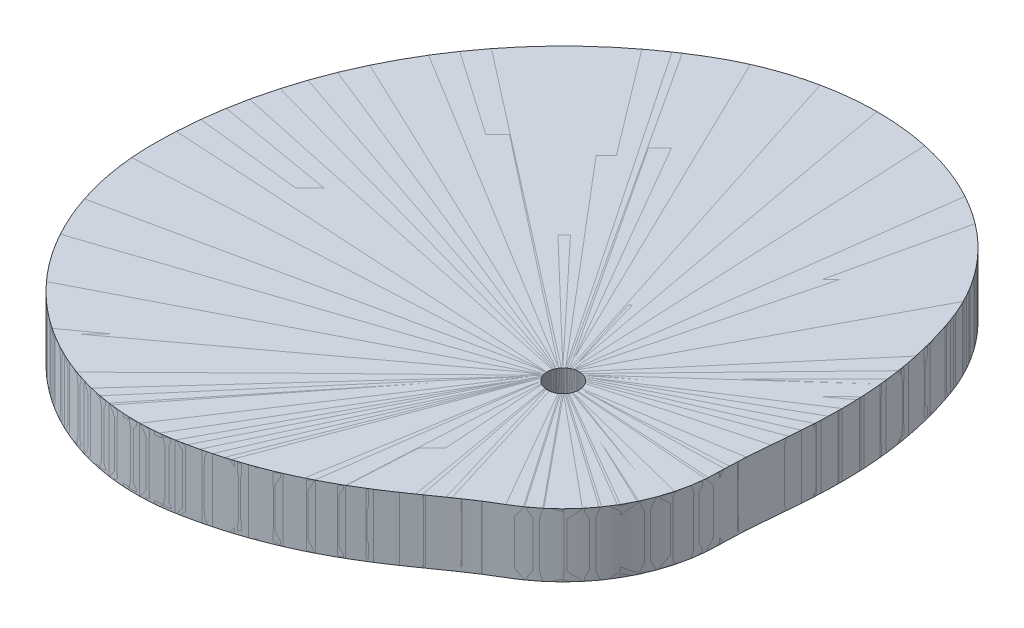
SolidWorks part; units mm, degrees
ref_plane "前视基准面" through (0, 0, 0) normal (0, 0, 1) x (1, 0, 0)
ref_plane "上视基准面" through (0, 0, 0) normal (0, 1, 0) x (1, 0, 0)
ref_plane "右视基准面" through (0, 0, 0) normal (1, 0, 0) x (0, 0, -1)
other "质心 (COM)"
other "Configuration Table"
sketch "草图1" plane through (0, 0, 0) normal (0, 0, 1) x (1, 0, 0)
  line L0 (0, -20200) -> (0, 200) construction
  line L1 (5, 0) -> (130, 0)
  line L2 (130, 0) -> (130, -20)
  line L3 (130, -20) -> (5, -20)
  line L4 (5, -20) -> (5, 0)
revolve "旋转1" add sketch "草图1" angle 360 about L0
sketch "草图2" plane through (0, 0, 0) normal (0, 1, 0) x (1, 0, 0)
  line L0 (0, 0) -> (50, 0) construction
  arc A0 (49.5, 0) -> (49.5868, 4.4012) centre (162.6884, -0.0309) cw
  arc A1 (49.5868, 4.4012) -> (49.8358, 8.9099) centre (194.8962, -1.3625) cw
  arc A2 (49.8358, 8.9099) -> (50.213, 13.6312) centre (319.2819, -10.2396) cw
  arc A3 (50.213, 13.6312) -> (50.663, 18.6649) centre (3915.5987, -329.3799) cw
  arc A4 (50.663, 18.6649) -> (51.1105, 24.1021) centre (-309.0879, 51.0135) ccw
  arc A5 (51.1105, 24.1021) -> (51.462, 30.0213) centre (-145.0959, 38.7218) ccw
  arc A6 (51.462, 30.0213) -> (51.6071, 36.4857) centre (-98.2755, 36.6179) ccw
  arc A7 (51.6071, 36.4857) -> (51.4215, 43.5396) centre (-79.0428, 36.5763) ccw
  arc A8 (51.4215, 43.5396) -> (50.7686, 51.2069) centre (-70.6967, 37.0025) ccw
  arc A9 (50.7686, 51.2069) -> (49.5032, 59.4882) centre (-67.8394, 37.3214) ccw
  arc A10 (49.5032, 59.4882) -> (47.4745, 68.3602) centre (-68.1876, 37.2436) ccw
  arc A11 (47.4745, 68.3602) -> (44.5307, 77.769) centre (-70.5306, 36.6049) ccw
  arc A12 (44.5307, 77.769) -> (40.298, 87.1155) centre (-14.8762, 56.4971) ccw
  arc A13 (40.298, 87.1155) -> (34.5682, 95.7489) centre (-16.8999, 55.3723) ccw
  arc A14 (34.5682, 95.7489) -> (27.4814, 103.4715) centre (-18.8355, 53.855) ccw
  arc A15 (27.4814, 103.4715) -> (19.2044, 110.1045) centre (-20.5276, 52.0448) ccw
  arc A16 (19.2044, 110.1045) -> (9.925, 115.4961) centre (-21.8914, 50.0559) ccw
  arc A17 (9.925, 115.4961) -> (-0.1518, 119.5233) centre (-22.8862, 48.016) ccw
  arc A18 (-0.1518, 119.5233) -> (-10.8076, 122.0939) centre (-23.5139, 46.0515) ccw
  arc A19 (-10.8076, 122.0939) -> (-21.8153, 123.1479) centre (-23.8137, 44.2768) ccw
  arc A20 (-21.8153, 123.1479) -> (-32.943, 122.6584) centre (-23.8548, 42.7851) ccw
  arc A21 (-32.943, 122.6584) -> (-43.9585, 120.6313) centre (-23.7281, 41.6427) ccw
  arc A22 (-43.9585, 120.6313) -> (-54.634, 117.105) centre (-23.5377, 40.8858) ccw
  arc A23 (-54.634, 117.105) -> (-64.75, 112.1503) centre (-23.3663, 40.4621) ccw
  arc A24 (-64.75, 112.1503) -> (-129.5, 0) centre (0, 0) ccw
  arc A25 (-129.5, 0) -> (-128.7329, -11.2381) centre (-46.7244, 0.0047) ccw
  arc A26 (-128.7329, -11.2381) -> (-126.449, -22.2464) centre (-47.177, -0.0586) ccw
  arc A27 (-126.449, -22.2464) -> (-122.6968, -32.7998) centre (-47.9277, -0.2722) ccw
  arc A28 (-122.6968, -32.7998) -> (-117.5569, -42.6814) centre (-48.9804, -0.7337) ccw
  arc A29 (-117.5569, -42.6814) -> (-111.1402, -51.6872) centre (-50.2517, -1.5152) ccw
  arc A30 (-111.1402, -51.6872) -> (-103.5861, -59.6302) centre (-51.6388, -2.6621) ccw
  arc A31 (-103.5861, -59.6302) -> (-95.0601, -66.3433) centre (-53.0262, -4.1879) ccw
  arc A32 (-95.0601, -66.3433) -> (-85.7511, -71.6838) centre (-54.2954, -6.0694) ccw
  arc A33 (-85.7511, -71.6838) -> (-75.8682, -75.5353) centre (-55.3359, -8.2449) ccw
  arc A34 (-75.8682, -75.5353) -> (-65.6369, -77.8113) centre (-56.0575, -10.6155) ccw
  arc A35 (-65.6369, -77.8113) -> (-55.2952, -78.4568) centre (-56.4038, -13.0504) ccw
  arc A36 (-55.2952, -78.4568) -> (-45.0846, -77.4492) centre (-56.366, -15.3653) ccw
  arc A37 (-45.0846, -77.4492) -> (-35.4644, -75.2942) centre (-66.9661, 42.7788) ccw
  arc A38 (-35.4644, -75.2942) -> (-26.7667, -72.6152) centre (-66.3477, 40.4304) ccw
  arc A39 (-26.7667, -72.6152) -> (-18.9621, -69.5703) centre (-66.241, 40.09) ccw
  arc A40 (-18.9621, -69.5703) -> (-11.9957, -66.3021) centre (-67.3934, 42.7239) ccw
  arc A41 (-11.9957, -66.3021) -> (-5.794, -62.9359) centre (-71.1974, 50.1649) ccw
  arc A42 (-5.794, -62.9359) -> (-0.2683, -59.578) centre (-80.8498, 66.8001) ccw
  arc A43 (-0.2683, -59.578) -> (4.6822, -56.314) centre (-106.082, 106.2959) ccw
  arc A44 (4.6822, -56.314) -> (9.1672, -53.2079) centre (-198.7229, 242.1712) ccw
  arc A45 (9.1672, -53.2079) -> (13.3016, -50.3013) centre (2243.0507, -3226.318) cw
  arc A46 (13.3016, -50.3013) -> (17.2017, -47.614) centre (168.5087, -271.3864) cw
  arc A47 (17.2017, -47.614) -> (20.9819, -45.144) centre (98.6281, -168.1038) cw
  arc A48 (20.9819, -45.144) -> (24.75, -42.8683) centre (81.371, -140.8768) cw
  arc A49 (24.75, -42.8683) -> (49.5, 0) centre (0, 0) ccw
extrude "切除-拉伸1" cut sketch "草图2" along normal blind 10 and the other way blind 30 flip side to cut
sketch "草图3" plane through (0, 0, 0) normal (0, 1, 0) x (1, 0, 0)
  circle A0 centre (0, 0) radius 5 construction
  circle A1 centre (0, 0) radius 5
  arc A50 (24.75, -42.8683) -> (20.9819, -45.144) centre (81.371, -140.8768) ccw
  arc A51 (24.75, -42.8683) -> (49.5, 0) centre (0, 0) ccw
  arc A52 (49.5868, 4.4012) -> (49.5, 0) centre (162.6884, -0.0309) ccw
  arc A53 (49.8358, 8.9099) -> (49.5868, 4.4012) centre (194.8962, -1.3625) ccw
  arc A54 (50.213, 13.6312) -> (49.8358, 8.9099) centre (319.2819, -10.2396) ccw
  arc A55 (50.663, 18.6649) -> (50.213, 13.6312) centre (3915.5987, -329.3799) ccw
  arc A56 (50.663, 18.6649) -> (51.1105, 24.1021) centre (-309.0879, 51.0135) ccw
  arc A57 (51.1105, 24.1021) -> (51.462, 30.0213) centre (-145.0959, 38.7218) ccw
  arc A58 (51.462, 30.0213) -> (51.6071, 36.4857) centre (-98.2755, 36.6179) ccw
  arc A59 (51.6071, 36.4857) -> (51.4215, 43.5396) centre (-79.0428, 36.5763) ccw
  arc A60 (51.4215, 43.5396) -> (50.7686, 51.2069) centre (-70.6967, 37.0025) ccw
  arc A61 (50.7686, 51.2069) -> (49.5032, 59.4882) centre (-67.8394, 37.3214) ccw
  arc A62 (49.5032, 59.4882) -> (47.4745, 68.3602) centre (-68.1876, 37.2436) ccw
  arc A63 (47.4745, 68.3602) -> (44.5307, 77.769) centre (-70.5306, 36.6049) ccw
  arc A64 (44.5307, 77.769) -> (40.298, 87.1155) centre (-14.8762, 56.4971) ccw
  arc A65 (40.298, 87.1155) -> (34.5682, 95.7489) centre (-16.8999, 55.3723) ccw
  arc A66 (34.5682, 95.7489) -> (27.4814, 103.4715) centre (-18.8355, 53.855) ccw
  arc A67 (27.4814, 103.4715) -> (19.2044, 110.1045) centre (-20.5276, 52.0448) ccw
  arc A68 (19.2044, 110.1045) -> (9.925, 115.4961) centre (-21.8914, 50.0559) ccw
  arc A69 (9.925, 115.4961) -> (-0.1518, 119.5233) centre (-22.8862, 48.016) ccw
  arc A70 (-0.1518, 119.5233) -> (-10.8076, 122.0939) centre (-23.5139, 46.0515) ccw
  arc A71 (-10.8076, 122.0939) -> (-21.8153, 123.1479) centre (-23.8137, 44.2768) ccw
  arc A72 (-21.8153, 123.1479) -> (-32.943, 122.6584) centre (-23.8548, 42.7851) ccw
  arc A73 (-32.943, 122.6584) -> (-43.9585, 120.6313) centre (-23.7281, 41.6427) ccw
  arc A74 (-43.9585, 120.6313) -> (-54.634, 117.105) centre (-23.5377, 40.8858) ccw
  arc A75 (-54.634, 117.105) -> (-64.75, 112.1503) centre (-23.3663, 40.4621) ccw
  arc A76 (-64.75, 112.1503) -> (-129.5, 0) centre (0, 0) ccw
  arc A77 (-129.5, 0) -> (-128.7329, -11.2381) centre (-46.7244, 0.0047) ccw
  arc A78 (-128.7329, -11.2381) -> (-126.449, -22.2464) centre (-47.177, -0.0586) ccw
  arc A79 (-126.449, -22.2464) -> (-122.6968, -32.7998) centre (-47.9277, -0.2722) ccw
  arc A80 (-122.6968, -32.7998) -> (-117.5569, -42.6814) centre (-48.9804, -0.7337) ccw
  arc A81 (-117.5569, -42.6814) -> (-111.1402, -51.6872) centre (-50.2517, -1.5152) ccw
  arc A82 (-111.1402, -51.6872) -> (-103.5861, -59.6302) centre (-51.6388, -2.6621) ccw
  arc A83 (-103.5861, -59.6302) -> (-95.0601, -66.3433) centre (-53.0262, -4.1879) ccw
  arc A84 (-95.0601, -66.3433) -> (-85.7511, -71.6838) centre (-54.2954, -6.0694) ccw
  arc A85 (-85.7511, -71.6838) -> (-75.8682, -75.5353) centre (-55.3359, -8.2449) ccw
  arc A86 (-75.8682, -75.5353) -> (-65.6369, -77.8113) centre (-56.0575, -10.6155) ccw
  arc A87 (-65.6369, -77.8113) -> (-55.2952, -78.4568) centre (-56.4038, -13.0504) ccw
  arc A88 (-55.2952, -78.4568) -> (-45.0846, -77.4492) centre (-56.366, -15.3653) ccw
  arc A89 (-45.0846, -77.4492) -> (-35.4644, -75.2942) centre (-66.9661, 42.7788) ccw
  arc A90 (-35.4644, -75.2942) -> (-26.7667, -72.6152) centre (-66.3477, 40.4304) ccw
  arc A91 (-26.7667, -72.6152) -> (-18.9621, -69.5703) centre (-66.241, 40.09) ccw
  arc A92 (-18.9621, -69.5703) -> (-11.9957, -66.3021) centre (-67.3934, 42.7239) ccw
  arc A93 (-11.9957, -66.3021) -> (-5.794, -62.9359) centre (-71.1974, 50.1649) ccw
  arc A94 (-5.794, -62.9359) -> (-0.2683, -59.578) centre (-80.8498, 66.8001) ccw
  arc A95 (-0.2683, -59.578) -> (4.6822, -56.314) centre (-106.082, 106.2959) ccw
  arc A96 (4.6822, -56.314) -> (9.1672, -53.2079) centre (-198.7229, 242.1712) ccw
  arc A97 (13.3016, -50.3013) -> (9.1672, -53.2079) centre (2243.0507, -3226.318) ccw
  arc A98 (17.2017, -47.614) -> (13.3016, -50.3013) centre (168.5087, -271.3864) ccw
  arc A99 (20.9819, -45.144) -> (17.2017, -47.614) centre (98.6281, -168.1038) ccw
  arc A100 (24.75, -42.8683) -> (20.9819, -45.144) centre (81.371, -140.8768) ccw construction
  arc A101 (24.75, -42.8683) -> (49.5, 0) centre (0, 0) ccw construction
  arc A102 (49.5868, 4.4012) -> (49.5, 0) centre (162.6884, -0.0309) ccw construction
  arc A103 (49.8358, 8.9099) -> (49.5868, 4.4012) centre (194.8962, -1.3625) ccw construction
  arc A104 (50.213, 13.6312) -> (49.8358, 8.9099) centre (319.2819, -10.2396) ccw construction
  arc A105 (50.663, 18.6649) -> (50.213, 13.6312) centre (3915.5987, -329.3799) ccw construction
  arc A106 (50.663, 18.6649) -> (51.1105, 24.1021) centre (-309.0879, 51.0135) ccw construction
  arc A107 (51.1105, 24.1021) -> (51.462, 30.0213) centre (-145.0959, 38.7218) ccw construction
  arc A108 (51.462, 30.0213) -> (51.6071, 36.4857) centre (-98.2755, 36.6179) ccw construction
  arc A109 (51.6071, 36.4857) -> (51.4215, 43.5396) centre (-79.0428, 36.5763) ccw construction
  arc A110 (51.4215, 43.5396) -> (50.7686, 51.2069) centre (-70.6967, 37.0025) ccw construction
  arc A111 (50.7686, 51.2069) -> (49.5032, 59.4882) centre (-67.8394, 37.3214) ccw construction
  arc A112 (49.5032, 59.4882) -> (47.4745, 68.3602) centre (-68.1876, 37.2436) ccw construction
  arc A113 (47.4745, 68.3602) -> (44.5307, 77.769) centre (-70.5306, 36.6049) ccw construction
  arc A114 (44.5307, 77.769) -> (40.298, 87.1155) centre (-14.8762, 56.4971) ccw construction
  arc A115 (40.298, 87.1155) -> (34.5682, 95.7489) centre (-16.8999, 55.3723) ccw construction
  arc A116 (34.5682, 95.7489) -> (27.4814, 103.4715) centre (-18.8355, 53.855) ccw construction
  arc A117 (27.4814, 103.4715) -> (19.2044, 110.1045) centre (-20.5276, 52.0448) ccw construction
  arc A118 (19.2044, 110.1045) -> (9.925, 115.4961) centre (-21.8914, 50.0559) ccw construction
  arc A119 (9.925, 115.4961) -> (-0.1518, 119.5233) centre (-22.8862, 48.016) ccw construction
  arc A120 (-0.1518, 119.5233) -> (-10.8076, 122.0939) centre (-23.5139, 46.0515) ccw construction
  arc A121 (-10.8076, 122.0939) -> (-21.8153, 123.1479) centre (-23.8137, 44.2768) ccw construction
  arc A122 (-21.8153, 123.1479) -> (-32.943, 122.6584) centre (-23.8548, 42.7851) ccw construction
  arc A123 (-32.943, 122.6584) -> (-43.9585, 120.6313) centre (-23.7281, 41.6427) ccw construction
  arc A124 (-43.9585, 120.6313) -> (-54.634, 117.105) centre (-23.5377, 40.8858) ccw construction
  arc A125 (-54.634, 117.105) -> (-64.75, 112.1503) centre (-23.3663, 40.4621) ccw construction
  arc A126 (-64.75, 112.1503) -> (-129.5, 0) centre (0, 0) ccw construction
  arc A127 (-129.5, 0) -> (-128.7329, -11.2381) centre (-46.7244, 0.0047) ccw construction
  arc A128 (-128.7329, -11.2381) -> (-126.449, -22.2464) centre (-47.177, -0.0586) ccw construction
  arc A129 (-126.449, -22.2464) -> (-122.6968, -32.7998) centre (-47.9277, -0.2722) ccw construction
  arc A130 (-122.6968, -32.7998) -> (-117.5569, -42.6814) centre (-48.9804, -0.7337) ccw construction
  arc A131 (-117.5569, -42.6814) -> (-111.1402, -51.6872) centre (-50.2517, -1.5152) ccw construction
  arc A132 (-111.1402, -51.6872) -> (-103.5861, -59.6302) centre (-51.6388, -2.6621) ccw construction
  arc A133 (-103.5861, -59.6302) -> (-95.0601, -66.3433) centre (-53.0262, -4.1879) ccw construction
  arc A134 (-95.0601, -66.3433) -> (-85.7511, -71.6838) centre (-54.2954, -6.0694) ccw construction
  arc A135 (-85.7511, -71.6838) -> (-75.8682, -75.5353) centre (-55.3359, -8.2449) ccw construction
  arc A136 (-75.8682, -75.5353) -> (-65.6369, -77.8113) centre (-56.0575, -10.6155) ccw construction
  arc A137 (-65.6369, -77.8113) -> (-55.2952, -78.4568) centre (-56.4038, -13.0504) ccw construction
  arc A138 (-55.2952, -78.4568) -> (-45.0846, -77.4492) centre (-56.366, -15.3653) ccw construction
  arc A139 (-45.0846, -77.4492) -> (-35.4644, -75.2942) centre (-66.9661, 42.7788) ccw construction
  arc A140 (-35.4644, -75.2942) -> (-26.7667, -72.6152) centre (-66.3477, 40.4304) ccw construction
  arc A141 (-26.7667, -72.6152) -> (-18.9621, -69.5703) centre (-66.241, 40.09) ccw construction
  arc A142 (-18.9621, -69.5703) -> (-11.9957, -66.3021) centre (-67.3934, 42.7239) ccw construction
  arc A143 (-11.9957, -66.3021) -> (-5.794, -62.9359) centre (-71.1974, 50.1649) ccw construction
  arc A144 (-5.794, -62.9359) -> (-0.2683, -59.578) centre (-80.8498, 66.8001) ccw construction
  arc A145 (-0.2683, -59.578) -> (4.6822, -56.314) centre (-106.082, 106.2959) ccw construction
  arc A146 (4.6822, -56.314) -> (9.1672, -53.2079) centre (-198.7229, 242.1712) ccw construction
  arc A147 (13.3016, -50.3013) -> (9.1672, -53.2079) centre (2243.0507, -3226.318) ccw construction
  arc A148 (17.2017, -47.614) -> (13.3016, -50.3013) centre (168.5087, -271.3864) ccw construction
  arc A149 (20.9819, -45.144) -> (17.2017, -47.614) centre (98.6281, -168.1038) ccw construction
  spline S0 degree 3 poles (20.0297, -45.7505) (19.3964, -46.1573) (18.7664, -46.569) (18.1396, -46.9855) (18.0351, -47.0549) (17.8263, -47.1941) (17.5136, -47.4034) (17.3056, -47.5437) (17.2017, -47.614) (17.0927, -47.6877) (16.8749, -47.8352) (16.5484, -48.057) (16.3309, -48.2052) (16.2223, -48.2794) (15.5703, -48.7244) (14.9202, -49.1723) (14.2722, -49.6231) (14.1642, -49.6982) (13.9482, -49.8486) (13.6246, -50.0745) (13.4092, -50.2257) (13.3016, -50.3013) (13.1867, -50.382) (12.9569, -50.5433) (12.6122, -50.7853) (12.3825, -50.9467) (12.2676, -51.0274) (11.5784, -51.5116) (10.8893, -51.9961) (10.2004, -52.4807) (9.9617, -52.6487) (9.4842, -52.9847) (8.768, -53.4888) (8.2897, -53.8236) (8.0504, -53.9908) (7.3048, -54.5113) (6.5573, -55.029) (5.8079, -55.5439) (5.683, -55.6297) (5.433, -55.8011) (5.0578, -56.0579) (4.8075, -56.2287) (4.6822, -56.314) (4.5461, -56.4068) (4.2738, -56.5921) (3.8641, -56.8686) (3.5907, -57.0523) (3.4539, -57.144) (2.6329, -57.6942) (1.8077, -58.2383) (0.9785, -58.776) (0.8403, -58.8657) (0.5637, -59.0446) (0.1481, -59.3119) (-0.1294, -59.4894) (-0.2683, -59.578) (-0.4197, -59.6746) (-0.7228, -59.8674) (-1.1789, -60.1545) (-1.4835, -60.3449) (-1.636, -60.4398) (-2.551, -61.0094) (-3.472, -61.5691) (-4.399, -62.1189) (-4.5535, -62.2105) (-4.8629, -62.3932) (-5.3278, -62.6655) (-5.6385, -62.846) (-5.794, -62.9359) (-5.9636, -63.0341) (-6.3034, -63.2298) (-6.8146, -63.5205) (-7.1562, -63.713) (-7.3272, -63.8088) (-8.3533, -64.3838) (-9.3871, -64.9449) (-10.4283, -65.4921) (-10.6019, -65.5832) (-10.9494, -65.7648) (-11.4718, -66.0348) (-11.8209, -66.2133) (-11.9957, -66.3021) (-12.1863, -66.399) (-12.5679, -66.5918) (-13.142, -66.8777) (-13.5257, -67.0663) (-13.7178, -67.1602) (-14.8704, -67.7232) (-16.0317, -68.268) (-17.2015, -68.7945) (-17.3964, -68.8822) (-17.7868, -69.0567) (-18.3737, -69.3153) (-18.7658, -69.4857) (-18.9621, -69.5703) (-19.1759, -69.6625) (-19.6038, -69.8456) (-20.2475, -70.1163) (-20.6776, -70.2944) (-20.8929, -70.3828) (-22.1849, -70.9131) (-23.486, -71.4207) (-24.7958, -71.9054) (-25.0141, -71.9862) (-25.4511, -72.1465) (-26.1081, -72.3831) (-26.547, -72.5382) (-26.7667, -72.6152) (-27.0053, -72.6987) (-27.4832, -72.8643) (-28.2015, -73.1082) (-28.6814, -73.2678) (-28.9216, -73.3468) (-30.3629, -73.8209) (-31.813, -74.2675) (-33.2713, -74.6865) (-33.5143, -74.7564) (-34.0008, -74.8945) (-34.7319, -75.0971) (-35.2201, -75.229) (-35.4644, -75.2942) (-35.7291, -75.3648) (-36.2589, -75.5042) (-37.055, -75.7081) (-37.5866, -75.8404) (-37.8527, -75.9056) (-39.449, -76.2972) (-41.0529, -76.6565) (-42.6637, -76.9834) (-42.9322, -77.0379) (-43.4694, -77.145) (-44.2764, -77.3003) (-44.8151, -77.4002) (-45.0846, -77.4492) (-45.3653, -77.5003) (-45.927, -77.6005) (-46.7726, -77.7344) (-47.3372, -77.8173) (-47.6197, -77.8568) (-49.3156, -78.0942) (-51.0197, -78.2623) (-52.7293, -78.361) (-53.0141, -78.3775) (-53.584, -78.4065) (-54.4395, -78.4386) (-55.0099, -78.452) (-55.2952, -78.4568) (-55.5833, -78.4617) (-56.1595, -78.4677) (-57.024, -78.4652) (-57.6001, -78.4559) (-57.8882, -78.4494) (-59.617, -78.4101) (-61.3428, -78.3024) (-63.0631, -78.1264) (-63.3444, -78.0976) (-63.9068, -78.0364) (-64.7492, -77.9337) (-65.3098, -77.8578) (-65.5898, -77.818) (-65.8836, -77.7764) (-66.4705, -77.6892) (-67.3494, -77.5468) (-67.9339, -77.4443) (-68.2258, -77.3911) (-69.9465, -77.0775) (-71.6539, -76.6977) (-73.3453, -76.2522) (-73.6171, -76.1806) (-74.16, -76.034) (-74.9716, -75.8041) (-75.5106, -75.644) (-75.7796, -75.5623) (-76.0716, -75.4736) (-76.6545, -75.2924) (-77.5254, -75.0093) (-78.1034, -74.813) (-78.3917, -74.713) (-80.0639, -74.133) (-81.713, -73.4903) (-83.3367, -72.7858) (-83.5937, -72.6744) (-84.1063, -72.4483) (-84.8713, -72.1002) (-85.3783, -71.8618) (-85.6311, -71.7412) (-85.9137, -71.6063) (-86.4772, -71.333) (-87.3173, -70.912) (-87.8735, -70.6241) (-88.1507, -70.4784) (-89.7358, -69.6453) (-91.2891, -68.7542) (-92.8084, -67.8064) (-93.0452, -67.6587) (-93.5172, -67.3605) (-94.2201, -66.9051) (-94.685, -66.596) (-94.9166, -66.4401) (-95.1829, -66.261) (-95.7131, -65.8992) (-96.5014, -65.3464) (-97.0222, -64.9712) (-97.2813, -64.7819) (-98.7435, -63.714) (-100.166, -62.5939) (-101.5471, -61.4231) (-101.7588, -61.2436) (-102.1803, -60.8823) (-102.8066, -60.3333) (-103.2199, -59.9626) (-103.4255, -59.7762) (-103.6691, -59.5553) (-104.1535, -59.1104) (-104.8716, -58.4337) (-105.3445, -57.9766) (-105.5794, -57.7465) (-106.8861, -56.467) (-108.1464, -55.1417) (-109.3589, -53.7725) (-109.5409, -53.5669) (-109.9028, -53.1538) (-110.4392, -52.5283) (-110.7921, -52.1075) (-110.9674, -51.8962) (-111.183, -51.6364) (-111.6107, -51.1142) (-112.2423, -50.3225) (-112.6565, -49.7894) (-112.8619, -49.5216) (-113.9844, -48.0575) (-115.055, -46.555) (-116.0722, -45.0159) (-116.2205, -44.7915) (-116.5147, -44.3412) (-116.9493, -43.6614) (-117.2343, -43.2052) (-117.3756, -42.9764) (-117.5585, -42.6802) (-117.9205, -42.0855) (-118.4519, -41.1863) (-118.7984, -40.5824) (-118.9696, -40.2793) (-119.8837, -38.6614) (-120.7413, -37.0128) (-121.5411, -35.3355) (-121.6521, -35.1028) (-121.8717, -34.6364) (-122.1946, -33.9336) (-122.4052, -33.463) (-122.5094, -33.2272) (-122.6562, -32.895) (-122.9454, -32.2286) (-123.3658, -31.2231) (-123.637, -30.5492) (-123.7704, -30.2114) (-124.4565, -28.4733) (-125.0825, -26.7127) (-125.6476, -24.9316) (-125.7181, -24.7093) (-125.8573, -24.2641) (-126.0603, -23.5945) (-126.1918, -23.147) (-126.2565, -22.9229) (-126.3651, -22.5476) (-126.5767, -21.7955) (-126.8782, -20.6626) (-127.0684, -19.9048) (-127.1608, -19.5252) (-127.6043, -17.7028) (-127.9853, -15.8663) (-128.3034, -14.0178) (-128.3479, -13.759) (-128.4345, -13.241) (-128.557, -12.4627) (-128.6336, -11.9432) (-128.6707, -11.6832) (-128.7219, -11.3238) (-128.8197, -10.6043) (-128.9522, -9.523) (-129.0311, -8.8011) (-129.0681, -8.44) (-129.2598, -6.5706) (-129.3878, -4.6958) (-129.4519, -2.8177) (-129.4625, -2.5047) (-129.4803, -1.8787) (-129.4977, -0.9394) (-129.5, -0.3131) (-129.5, 0) (-129.5, 0.314) (-129.4977, 0.942) (-129.4874, 1.8841) (-129.476, 2.512) (-129.4692, 2.8259) (-128.4819, 48.0581) (-105.8604, 87.2395) (-67.1819, 110.7106) (-66.9135, 110.8735) (-66.3754, 111.1974) (-65.5647, 111.6773) (-65.0219, 111.9933) (-64.75, 112.1503) (-64.4788, 112.3069) (-63.9354, 112.618) (-63.1131, 113.0726) (-62.5621, 113.3702) (-62.2858, 113.5174) (-60.6272, 114.401) (-58.9396, 115.2276) (-57.2248, 115.9962) (-56.8935, 116.1448) (-56.229, 116.4374) (-55.2263, 116.8633) (-54.5543, 117.1384) (-54.2174, 117.2737) (-53.9737, 117.3716) (-53.4854, 117.565) (-52.7502, 117.8481) (-52.2583, 118.0321) (-52.0119, 118.1229) (-50.2521, 118.7717) (-48.4711, 119.36) (-46.6711, 119.8871) (-46.2961, 119.9968) (-45.5447, 120.2111) (-44.4129, 120.5164) (-43.6557, 120.7092) (-43.2764, 120.8028) (-43.05, 120.8588) (-42.5967, 120.9687) (-41.9153, 121.1276) (-41.4602, 121.2297) (-41.2324, 121.2798) (-39.4074, 121.6809) (-37.5696, 122.0191) (-35.7214, 122.294) (-35.3621, 122.3474) (-34.6429, 122.4494) (-33.5619, 122.5881) (-32.8402, 122.6709) (-32.4791, 122.7099) (-32.2228, 122.7375) (-31.71, 122.7904) (-30.9399, 122.8622) (-30.4261, 122.9052) (-30.1691, 122.9254) (-28.3166, 123.0714) (-26.4601, 123.1531) (-24.6019, 123.1703) (-24.2538, 123.1736) (-23.5576, 123.1755) (-22.5132, 123.1649) (-21.8171, 123.1487) (-21.4692, 123.1384) (-21.2004, 123.1304) (-20.6628, 123.1118) (-19.8567, 123.0753) (-19.3197, 123.0456) (-19.0512, 123.0294) (-17.2097, 122.918) (-15.3732, 122.7422) (-13.544, 122.502) (-13.2093, 122.4581) (-12.5406, 122.3659) (-11.5392, 122.2148) (-10.873, 122.1055) (-10.5403, 122.0487) (-10.2696, 122.0025) (-9.7287, 121.9073) (-8.9189, 121.7555) (-8.3801, 121.6487) (-8.1111, 121.5938) (-6.3191, 121.2284) (-4.5412, 120.7995) (-2.7798, 120.3077) (-2.463, 120.2193) (-1.8307, 120.0383) (-0.8857, 119.7548) (-0.2582, 119.5577) (0.0549, 119.4572) (0.3192, 119.3724) (0.8469, 119.1998) (1.6354, 118.9319) (2.1591, 118.7475) (2.4204, 118.6539) (4.1249, 118.0433) (5.8062, 117.3714) (7.4621, 116.639) (7.7556, 116.5092) (8.3409, 116.2459) (9.2139, 115.8396) (9.7922, 115.5613) (10.0805, 115.4203) (10.3313, 115.2976) (10.8314, 115.0495) (11.5773, 114.6685) (12.0715, 114.4089) (12.3179, 114.2776) (13.8984, 113.4357) (15.4467, 112.5361) (16.9608, 111.58) (17.2255, 111.4128) (17.7529, 111.075) (18.5376, 110.5579) (19.0561, 110.2066) (19.3142, 110.0293) (19.545, 109.8707) (20.0049, 109.5507) (20.6889, 109.0623) (21.141, 108.7314) (21.366, 108.5646) (22.7879, 107.5107) (24.1691, 106.4038) (25.5075, 105.2457) (25.7383, 105.046) (26.1972, 104.6436) (26.8779, 104.031) (27.3263, 103.6168) (27.5491, 103.4082) (27.7543, 103.2161) (28.1625, 102.8294) (28.7674, 102.2414) (29.1658, 101.8446) (29.3637, 101.645) (30.5952, 100.4029) (31.7778, 99.1142) (32.9098, 97.7808) (33.1018, 97.5546) (33.4828, 97.0997) (34.0455, 96.4098) (34.4145, 95.945) (34.5975, 95.7115) (34.7719, 95.4888) (35.118, 95.0413) (35.6281, 94.3631) (35.9623, 93.9067) (36.1279, 93.6774) (37.1405, 92.2757) (38.0967, 90.8349) (38.9951, 89.3573) (39.1447, 89.1111) (39.4409, 88.6168) (39.8753, 87.8694) (40.1582, 87.3674) (40.298, 87.1155) (40.4365, 86.866) (40.7101, 86.3653) (41.11, 85.6083) (41.3698, 85.1003) (41.498, 84.8454) (42.2673, 83.3155) (42.9737, 81.7556) (43.6161, 80.1683) (43.7232, 79.9038) (43.9336, 79.3735) (44.2405, 78.5742) (44.4346, 78.0376) (44.5307, 77.769) (44.623, 77.5111) (44.8058, 76.9946) (45.0748, 76.2181) (45.2507, 75.6993) (45.3377, 75.4395) (45.86, 73.8811) (46.3508, 72.3124) (46.8099, 70.7342) (46.8864, 70.4712) (47.0376, 69.9446) (47.2592, 69.1532) (47.4033, 68.6247) (47.4745, 68.3602) (47.5402, 68.116) (47.6701, 67.6272) (47.8601, 66.8928) (47.9837, 66.4024) (48.0448, 66.157) (48.4111, 64.6846) (48.7493, 63.2055) (49.0594, 61.7203) (49.111, 61.4727) (49.2128, 60.9774) (49.3608, 60.2333) (49.4563, 59.7367) (49.5032, 59.4882) (49.5465, 59.2595) (49.6316, 58.8018) (49.7551, 58.1146) (49.8348, 57.6559) (49.874, 57.4265) (50.1091, 56.0498) (50.3201, 54.6693) (50.5068, 53.2852) (50.5379, 53.0545) (50.5988, 52.593) (50.6862, 51.9002) (50.7416, 51.438) (50.7686, 51.2069) (50.7934, 50.9945) (50.842, 50.5697) (50.9115, 49.9321) (50.9555, 49.5068) (50.977, 49.2941) (51.106, 48.0179) (51.2148, 46.7397) (51.3035, 45.46) (51.3183, 45.2468) (51.3467, 44.8202) (51.3862, 44.18) (51.4101, 43.7531) (51.4215, 43.5396) (51.4319, 43.3439) (51.4519, 42.9523) (51.4793, 42.3648) (51.4958, 41.9731) (51.5036, 41.7772) (51.5504, 40.6019) (51.5814, 39.4261) (51.5964, 38.2499) (51.599, 38.0539) (51.6031, 37.6619) (51.6069, 37.0738) (51.6073, 36.6817) (51.6071, 36.4857) (51.607, 36.3061) (51.606, 35.9468) (51.6026, 35.4079) (51.5991, 35.0487) (51.597, 34.8691) (51.5844, 33.7914) (51.5602, 32.7139) (51.5244, 31.6367) (51.5184, 31.4572) (51.5058, 31.0982) (51.4853, 30.5597) (51.4699, 30.2008) (51.462, 30.0213) (51.4547, 29.8568) (51.4397, 29.5277) (51.416, 29.0341) (51.3993, 28.7051) (51.3908, 28.5406) (51.3397, 27.5536) (51.2811, 26.567) (51.2151, 25.5809) (51.2041, 25.4165) (51.1817, 25.0878) (51.1471, 24.5949) (51.1228, 24.2663) (51.1105, 24.1021) (51.0992, 23.951) (51.0764, 23.6487) (51.0417, 23.1954) (51.0182, 22.8932) (51.0063, 22.7422) (50.9352, 21.8357) (50.8606, 20.9295) (50.7825, 20.0236) (50.7575, 19.7327) (50.7067, 19.1511) (50.6282, 18.2788) (50.5759, 17.6973) (50.5499, 17.4065) (50.4746, 16.5676) (50.3996, 15.7286) (50.3249, 14.8897) (50.3124, 14.7498) (50.2875, 14.4702) (50.2502, 14.0507) (50.2254, 13.771) (50.213, 13.6312) (50.2013, 13.5001) (50.1781, 13.238) (50.1443, 12.8448) (50.122, 12.5826) (50.1109, 12.4515) (50.0446, 11.6649) (49.9817, 10.878) (49.9223, 10.0908) (49.9124, 9.9596) (49.8928, 9.6972) (49.864, 9.3036) (49.8451, 9.0411) (49.8358, 8.9099) (49.8269, 8.7847) (49.8093, 8.5345) (49.7844, 8.159) (49.7683, 7.9086) (49.7604, 7.7834) (49.7131, 7.0323) (49.6716, 6.2808) (49.6359, 5.529) (49.63, 5.4037) (49.6184, 5.1531) (49.602, 4.7772) (49.5918, 4.5265) (49.5868, 4.4012) (49.582, 4.279) (49.5726, 4.0346) (49.5603, 3.6679) (49.5527, 3.4235) (49.5491, 3.3013) (49.5275, 2.5678) (49.513, 1.8343) (49.5057, 1.1006) (49.5032, 0.8557) (49.4999, 0.3658) (49.5004, -0.369) (49.4932, -0.8588) (49.4877, -1.1036) (49.1025, -18.3752) (40.4646, -33.3365) (25.6996, -42.3058) (25.4903, -42.4329) (25.0698, -42.6842) (24.4331, -43.0511) (24.0106, -43.2989) (23.7997, -43.4234) (23.168, -43.7966) (22.5399, -44.176) (21.9156, -44.5614) (21.8115, -44.6256) (21.6036, -44.7544) (21.2922, -44.9484) (21.0853, -45.0787) (20.9819, -45.144) (20.8758, -45.211) (20.6639, -45.3452) (20.3465, -45.5474) (20.1352, -45.6827) (20.0297, -45.7505) (19.3964, -46.1573) (18.7664, -46.569) knots -0.000629 0 0 0 0.003777 0.003777 0.003777 0.004406 0.005036 0.005665 0.005665 0.005665 0.006325 0.006985 0.007646 0.007646 0.007646 0.011607 0.011607 0.011607 0.012267 0.012927 0.013588 0.013588 0.013588 0.014292 0.014997 0.015701 0.015701 0.015701 0.019928 0.019928 0.019928 0.021393 0.022858 0.024323 0.024323 0.024323 0.028885 0.028885 0.028885 0.029646 0.030406 0.031167 0.031167 0.031167 0.031993 0.03282 0.033646 0.033646 0.033646 0.038606 0.038606 0.038606 0.039432 0.040259 0.041086 0.041086 0.041086 0.041987 0.042888 0.04379 0.04379 0.04379 0.049198 0.049198 0.049198 0.050099 0.051001 0.051902 0.051902 0.051902 0.052886 0.053869 0.054853 0.054853 0.054853 0.060755 0.060755 0.060755 0.061739 0.062723 0.063706 0.063706 0.063706 0.064779 0.065852 0.066925 0.066925 0.066925 0.073361 0.073361 0.073361 0.074434 0.075507 0.07658 0.07658 0.07658 0.077748 0.078916 0.080084 0.080084 0.080084 0.087091 0.087091 0.087091 0.088259 0.089427 0.090595 0.090595 0.090595 0.091864 0.093133 0.094402 0.094402 0.094402 0.102015 0.102015 0.102015 0.103284 0.104552 0.105821 0.105821 0.105821 0.107196 0.10857 0.109945 0.109945 0.109945 0.118192 0.118192 0.118192 0.119566 0.120941 0.122316 0.122316 0.122316 0.123747 0.125179 0.126611 0.126611 0.126611 0.135199 0.135199 0.135199 0.13663 0.138062 0.139494 0.139494 0.139494 0.14094 0.142385 0.143831 0.143831 0.143831 0.152504 0.152504 0.152504 0.153923 0.155343 0.156762 0.156762 0.156762 0.158251 0.15974 0.161228 0.161228 0.161228 0.170001 0.170001 0.170001 0.171412 0.172823 0.174233 0.174233 0.174233 0.175765 0.177296 0.178828 0.178828 0.178828 0.187705 0.187705 0.187705 0.189111 0.190517 0.191922 0.191922 0.191922 0.193494 0.195065 0.196636 0.196636 0.196636 0.205618 0.205618 0.205618 0.207019 0.20842 0.209821 0.209821 0.209821 0.211431 0.213041 0.214652 0.214652 0.214652 0.223733 0.223733 0.223733 0.225126 0.226519 0.227912 0.227912 0.227912 0.229562 0.231212 0.232862 0.232862 0.232862 0.242036 0.242036 0.242036 0.243414 0.244792 0.24617 0.24617 0.24617 0.247864 0.249557 0.251251 0.251251 0.251251 0.260505 0.260505 0.260505 0.261855 0.263204 0.264554 0.264554 0.264554 0.266301 0.268047 0.269794 0.269794 0.269794 0.279115 0.279115 0.279115 0.280409 0.281703 0.282996 0.282996 0.282996 0.284819 0.286641 0.288464 0.288464 0.288464 0.297837 0.297837 0.297837 0.299007 0.300178 0.301348 0.301348 0.301348 0.303308 0.305269 0.307229 0.307229 0.307229 0.316638 0.316638 0.316638 0.317955 0.319273 0.320591 0.320591 0.320591 0.322413 0.324234 0.326056 0.326056 0.326056 0.335483 0.335483 0.335483 0.337054 0.338625 0.340196 0.340196 0.340196 0.341772 0.343348 0.344924 0.344924 0.344924 0.553299 0.553299 0.553299 0.554875 0.556451 0.558027 0.558027 0.558027 0.559598 0.561169 0.56274 0.56274 0.56274 0.572167 0.572167 0.572167 0.573989 0.57581 0.577632 0.577632 0.577632 0.57895 0.580268 0.581585 0.581585 0.581585 0.590994 0.590994 0.590994 0.592954 0.594915 0.596875 0.596875 0.596875 0.598045 0.599216 0.600386 0.600386 0.600386 0.609759 0.609759 0.609759 0.611582 0.613404 0.615227 0.615227 0.615227 0.61652 0.617814 0.619107 0.619107 0.619107 0.628429 0.628429 0.628429 0.630176 0.631922 0.633669 0.633669 0.633669 0.635019 0.636368 0.637718 0.637718 0.637718 0.646972 0.646972 0.646972 0.648666 0.650359 0.652053 0.652053 0.652053 0.653431 0.654809 0.656187 0.656187 0.656187 0.665361 0.665361 0.665361 0.667011 0.668661 0.670311 0.670311 0.670311 0.671704 0.673097 0.67449 0.67449 0.67449 0.683571 0.683571 0.683571 0.685182 0.686792 0.688402 0.688402 0.688402 0.689803 0.691204 0.692605 0.692605 0.692605 0.701587 0.701587 0.701587 0.703158 0.704729 0.706301 0.706301 0.706301 0.707706 0.709112 0.710518 0.710518 0.710518 0.719395 0.719395 0.719395 0.720927 0.722458 0.72399 0.72399 0.72399 0.7254 0.726811 0.728222 0.728222 0.728222 0.736995 0.736995 0.736995 0.738483 0.739972 0.741461 0.741461 0.741461 0.74288 0.7443 0.745719 0.745719 0.745719 0.754392 0.754392 0.754392 0.755838 0.757283 0.758729 0.758729 0.758729 0.760161 0.761593 0.763024 0.763024 0.763024 0.771612 0.771612 0.771612 0.773044 0.774476 0.775907 0.775907 0.775907 0.777282 0.778657 0.780031 0.780031 0.780031 0.788278 0.788278 0.788278 0.789653 0.791027 0.792402 0.792402 0.792402 0.793671 0.794939 0.796208 0.796208 0.796208 0.803821 0.803821 0.803821 0.80509 0.806359 0.807628 0.807628 0.807628 0.808796 0.809964 0.811132 0.811132 0.811132 0.818139 0.818139 0.818139 0.819307 0.820475 0.821643 0.821643 0.821643 0.822716 0.823789 0.824862 0.824862 0.824862 0.831298 0.831298 0.831298 0.832371 0.833444 0.834517 0.834517 0.834517 0.8355 0.836484 0.837468 0.837468 0.837468 0.84337 0.84337 0.84337 0.844354 0.845337 0.846321 0.846321 0.846321 0.847222 0.848124 0.849025 0.849025 0.849025 0.854433 0.854433 0.854433 0.855335 0.856236 0.857137 0.857137 0.857137 0.857964 0.85879 0.859617 0.859617 0.859617 0.864577 0.864577 0.864577 0.865403 0.86623 0.867056 0.867056 0.867056 0.867817 0.868577 0.869338 0.869338 0.869338 0.8739 0.8739 0.8739 0.875365 0.87683 0.878295 0.878295 0.878295 0.882522 0.882522 0.882522 0.883226 0.883931 0.884635 0.884635 0.884635 0.885296 0.885956 0.886616 0.886616 0.886616 0.890577 0.890577 0.890577 0.891238 0.891898 0.892558 0.892558 0.892558 0.893187 0.893817 0.894446 0.894446 0.894446 0.898223 0.898223 0.898223 0.898852 0.899482 0.900111 0.900111 0.900111 0.900725 0.901339 0.901952 0.901952 0.901952 0.905634 0.905634 0.905634 0.906863 0.908092 0.909321 0.909321 0.909321 0.988902 0.988902 0.988902 0.990131 0.99136 0.992589 0.992589 0.992589 0.996271 0.996271 0.996271 0.996884 0.997498 0.998112 0.998112 0.998112 0.998741 0.999371 1 1 1 1.003777 1.003777 1.003777 weights 1 0.99998 0.99998 1 1 1 1 1 1 1 1 1 1 1 0.999994 0.999994 1 1 1 1 1 1 1 1 1 1 1 1 1 1 1 1 1 1 1 0.999995 0.999995 1 1 1 1 1 1 1 1 1 1 1 0.999981 0.999981 1 1 1 1 1 1 1 1 1 1 1 0.999961 0.999961 1 1 1 1 1 1 1 1 1 1 1 0.999939 0.999939 1 1 1 1 1 1 1 1 1 1 1 0.999917 0.999917 1 1 1 1 1 1 1 1 1 1 1 0.999897 0.999897 1 1 1 1 1 1 1 1 1 1 1 0.99988 0.99988 1 1 1 1 1 1 1 1 1 1 1 0.999864 0.999864 1 1 1 1 1 1 1 1 1 1 1 0.999448 0.999448 1 1 1 1 1 1 1 1 1 1 1 0.999476 0.999476 1 1 1 1 1 1 1 1 1 1 1 0.999502 0.999502 1 1 1 1 1 1 1 1 1 1 1 0.999526 0.999526 1 1 1 1 1 1 1 1 1 1 1 0.999546 0.999546 1 1 1 1 1 1 1 1 1 1 1 0.999564 0.999564 1 1 1 1 1 1 1 1 1 1 1 0.999578 0.999578 1 1 1 1 1 1 1 1 1 1 1 0.99959 0.99959 1 1 1 1 1 1 1 1 1 1 1 0.999599 0.999599 1 1 1 1 1 1 1 1 1 1 1 0.999606 0.999606 1 1 1 1 1 1 1 1 1 1 1 0.999611 0.999611 1 1 1 1 1 1 1 1 1 1 1 0.999614 0.999614 1 1 1 1 1 1 1 1 1 1 1 0.91782 0.91782 1 1 1 1 1 1 1 1 1 1 1 0.999614 0.999614 1 1 1 1 1 1 1 1 1 1 1 0.999611 0.999611 1 1 1 1 1 1 1 1 1 1 1 0.999606 0.999606 1 1 1 1 1 1 1 1 1 1 1 0.999599 0.999599 1 1 1 1 1 1 1 1 1 1 1 0.99959 0.99959 1 1 1 1 1 1 1 1 1 1 1 0.999578 0.999578 1 1 1 1 1 1 1 1 1 1 1 0.999564 0.999564 1 1 1 1 1 1 1 1 1 1 1 0.999546 0.999546 1 1 1 1 1 1 1 1 1 1 1 0.999526 0.999526 1 1 1 1 1 1 1 1 1 1 1 0.999502 0.999502 1 1 1 1 1 1 1 1 1 1 1 0.999476 0.999476 1 1 1 1 1 1 1 1 1 1 1 0.999448 0.999448 1 1 1 1 1 1 1 1 1 1 1 0.999864 0.999864 1 1 1 1 1 1 1 1 1 1 1 0.99988 0.99988 1 1 1 1 1 1 1 1 1 1 1 0.999897 0.999897 1 1 1 1 1 1 1 1 1 1 1 0.999917 0.999917 1 1 1 1 1 1 1 1 1 1 1 0.999939 0.999939 1 1 1 1 1 1 1 1 1 1 1 0.999961 0.999961 1 1 1 1 1 1 1 1 1 1 1 0.999981 0.999981 1 1 1 1 1 1 1 1 1 1 1 0.999995 0.999995 1 1 1 1 1 1 1 1 1 1 1 1 1 1 1 1 1 1 1 0.999994 0.999994 1 1 1 1 1 1 1 1 1 1 1 0.99998 0.99998 1 1 1 1 1 1 1 1 1 1 1 0.999968 0.999968 1 1 1 1 1 1 0.917972 0.917972 1 1 1 1 1 1 0.999968 0.999968 1 1 1 1 1 1 1 1 1 1 1 0.99998 0.99998 only from (20.0297, -45.7505) to (20.0297, -45.7505)
  dimension "D1" = 0
extrude "凸台-拉伸1" add sketch "草图3" against normal up to surface (20 mm away) separate body up to face at (-14.6176, -20, -8.4395)
